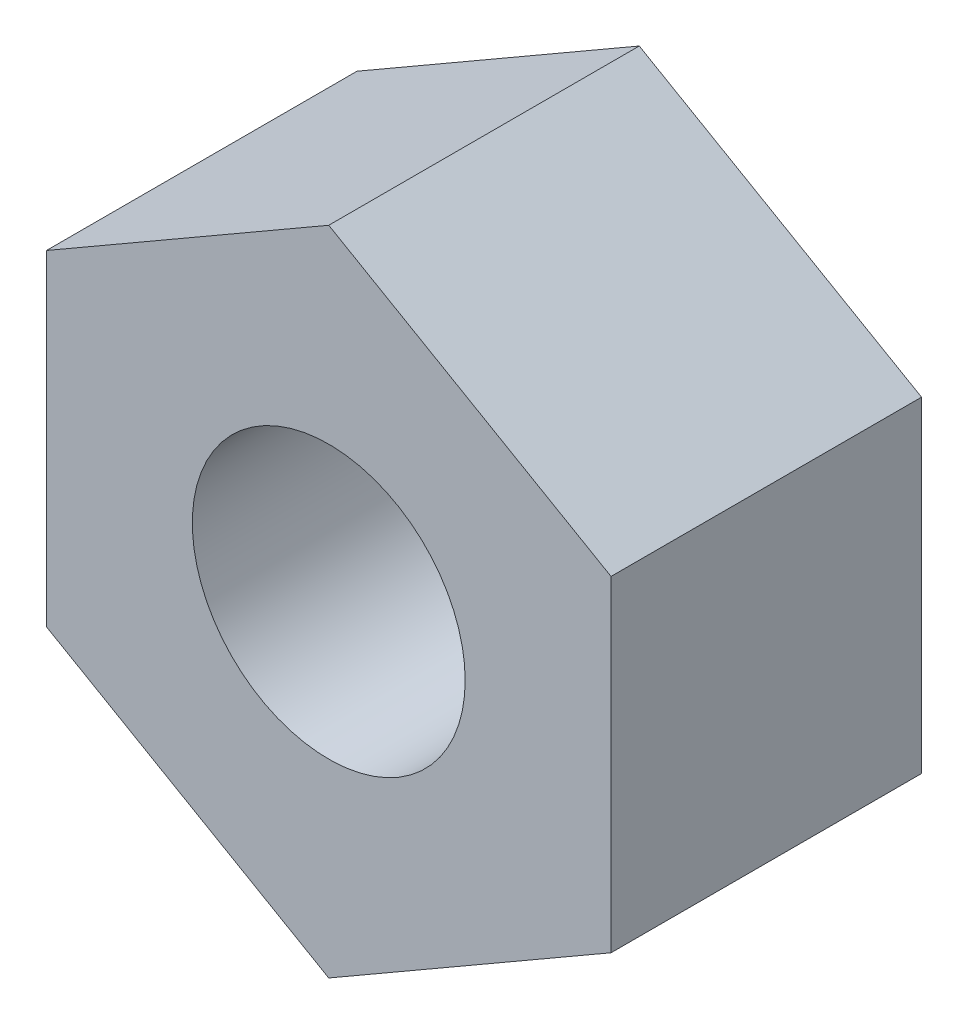
SolidWorks part; units mm, degrees
extrude "BaseNut" add sketch "BaseNutSke" against normal blind 3.3
sketch "BaseNutSke" plane through (0, 0, 0) normal (0, 0, 1) x (1, 0, 0)
  line L6 (3, 1.7321) -> (3, -1.7321)
  line L7 (-3, 1.7321) -> (-3, -1.7321)
  line L8 (3, 1.7321) -> (0, 3.4641)
  line L9 (0, 3.4641) -> (-3, 1.7321)
  line L10 (-3, -1.7321) -> (0, -3.4641)
  line L11 (0, -3.4641) -> (3, -1.7321)
  circle A0 centre (0, 0) radius 1.45
  dimension "Tap_drill" = 2.9
  dimension "Width_flats" = 6
  dimension "D2" = 3
  dimension "D3" = 3
  dimension "D1" = 120
  dimension "D4" = 3
cosmetic thread "ThreadCosmetic" [suppressed] parameters "Thread_major"=3.5
pattern_linear "ThdSchPat" [suppressed]
revolve "ThreadSchematic" [suppressed] cut sketch "ThdSchSke" angle 360 about L6
sketch "ThdSchSke" plane through (0, 0, 0) normal (0, 1, 0) x (1, 0, 0)
  line L0 (-1.75, 0.0254) -> (-1.45, 0.2355)
  line L1 (-1.45, 0.2355) -> (-0.725, 0.2355)
  line L2 (-0.725, 0.2355) -> (-0.725, -0.1847)
  line L3 (-0.725, -0.1847) -> (-1.45, -0.1847)
  line L4 (-1.45, -0.1847) -> (-1.75, 0.0254)
  line L5 (-3.175, 0.6) -> (3.175, 0.6) construction
  line L6 (0, 0.6) -> (0, -2.9874) construction
  line L7 (0, 3.3) -> (0, 0) construction
  dimension "Thread_major" = 3.5
  dimension "SideAngle" = 55
  dimension "Advance" = 0.6
  dimension "D1" = 0.0254
ref_plane "Plane1" through (0, 0, 0) normal (0, 0, 1) x (1, 0, 0)
ref_plane "Plane2" through (0, 0, 0) normal (0, 1, 0) x (1, 0, 0)
ref_plane "Plane3" through (0, 0, 0) normal (1, 0, 0) x (0, 0, -1)
sketch "Sketch4" plane through (0, 0, 0) normal (1, 0, 0) x (0, 0, -1)
  line L0 (3.3, 3) -> (3.29, 3)
  line L1 (3.3, 3) -> (3.3, 13.4641)
  line L2 (3.29, 13.4641) -> (3.3, 13.4641)
  line L3 (3.29, 13.4641) -> (3.29, 3)
  line L4 (0, 0) -> (34.925, 0) construction
  line L6 (3.3, 1.7321) -> (3.3, 3.4641) construction
  line L7 (0, 3) -> (-10, 3)
  line L8 (0, 1.7321) -> (0, 3.4641) construction
  line L9 (0.2679, 3.4641) -> (0.2679, 13.4641)
  line L10 (0.2679, 13.4641) -> (-10, 13.4641)
  line L11 (-10, 13.4641) -> (-10, 3)
  line L12 (0, 3) -> (0.2679, 3.4641)
  line L14 (0, 1.7321) -> (0, -1.7321) construction
  line L15 (3.3, 3.4641) -> (0, 3.4641) construction
  dimension "D1" = 3
  dimension "D4" = 10
  dimension "D3" = 10
  dimension "D2" = 30
revolve "Bearing-Face" [suppressed] cut sketch "Sketch4" angle 360 about L4
sketch "Sketch3" plane through (0, 0, 0) normal (1, 0, 0) x (0, 0, -1)
  line L0 (3.3, 3) -> (3.0321, 3.4641)
  line L1 (3.0321, 3.4641) -> (3.0321, 13.4641)
  line L2 (3.0321, 13.4641) -> (13.3, 13.4641)
  line L3 (13.3, 13.4641) -> (13.3, 3)
  line L4 (13.3, 3) -> (3.3, 3)
  line L5 (3.3, 1.7321) -> (3.3, 3.4641) construction
  line L6 (3.3, 3.4641) -> (0, 3.4641) construction
  line L7 (0, 0) -> (38.6776, 0) construction
  line L8 (3.3, 0) -> (0, 0) construction
  line L9 (1.65, 3.4641) -> (1.65, 44.222) construction
  line L10 (0.2679, 13.4641) -> (-10, 13.4641)
  line L11 (-10, 13.4641) -> (-10, 3)
  line L12 (-10, 3) -> (0, 3)
  line L13 (0, 3) -> (0.2679, 3.4641)
  line L14 (0.2679, 3.4641) -> (0.2679, 13.4641)
  line L16 (3.3, 3.4641) -> (0, 3.4641) construction
  dimension "D1" = 3
  dimension "D4" = 10
  dimension "D3" = 10
  dimension "D2" = 30
sketch "Sketch5" plane through (0, 0, 0) normal (1, 0, 0) x (0, 0, -1)
  line L0 (3.2746, 1.75) -> (3.0435, 1.42)
  line L1 (3.3254, 1.75) -> (3.2746, 1.75)
  line L2 (3.3254, 1.75) -> (3.3254, 1.42)
  line L3 (3.3254, 1.42) -> (3.0435, 1.42)
  line L6 (-0.0508, 1.75) -> (0, 1.75)
  line L7 (0, 1.75) -> (0.2311, 1.42)
  line L9 (0.2311, 1.42) -> (-0.0508, 1.42)
  line L10 (-0.0508, 1.42) -> (-0.0508, 1.75)
  line L11 (25.0375, 0) -> (38.388, 0) construction
  line L12 (3.3, 0) -> (0, 0) construction
  dimension "D1" = 35
  dimension "D2" = 0.0508
  dimension "ThreadMajor" = 1.75
  dimension "Offset1" = 3.3254
equation "\"D2@BaseNutSke\" = \"Width_flats@BaseNutSke\" / 2"
equation "\"D3@BaseNutSke\" = \"Width_flats@BaseNutSke\" / 2"
equation "\"D1@Sketch3\" = \"Width_flats@BaseNutSke\" /2"
equation "\"D1@Sketch4\" = \"D2@BaseNutSke\""
equation "\"D4@BaseNutSke\" = \"D3@BaseNutSke\""
equation "\"Thread_major@ThdSchSke\" = \"Thread_major@ThreadCosmetic\""
equation "\"Tap_Drill@ThdSchSke\" = \"Tap_drill@BaseNutSke\""
equation "\"OverCut@ThdSchSke\" = \"Tap_Drill@ThdSchSke\" * 0.5"
equation "\"Num_threads@ThdSchPat\" = int(  ( \"Thickness@BaseNut\" - 0.0508 ) / \"Advance@ThdSchSke\" + 0.999 )  + 1"
equation "\"Advance@ThdSchPat\" = ( \"Thickness@BaseNut\" - 0.0508 ) /  (\"Num_threads@ThdSchPat\" - 1) 'relax it"
equation "' \"Num_threads@ThdSchPat\" = \"Num_threads@ThdSchPat\" - sgn( \"Num_threads@ThdSchPat\" - 1) '---chamfered tips only---"
equation "\"ThreadMajor@Sketch5\" = \"Thread_major@ThreadCosmetic\" * 0.5"
equation "\"ChamferDepth@Sketch5\" = (\"Thread_major@ThreadCosmetic\" - \"Tap_drill@BaseNutSke\") * 0.55"
equation "\"Offset1@Sketch5\" = \"Thickness@BaseNut\" + 0.0254"
equation "\"Offset2@Sketch5\" = \"Offset1@Sketch5\" + 0.0508"
